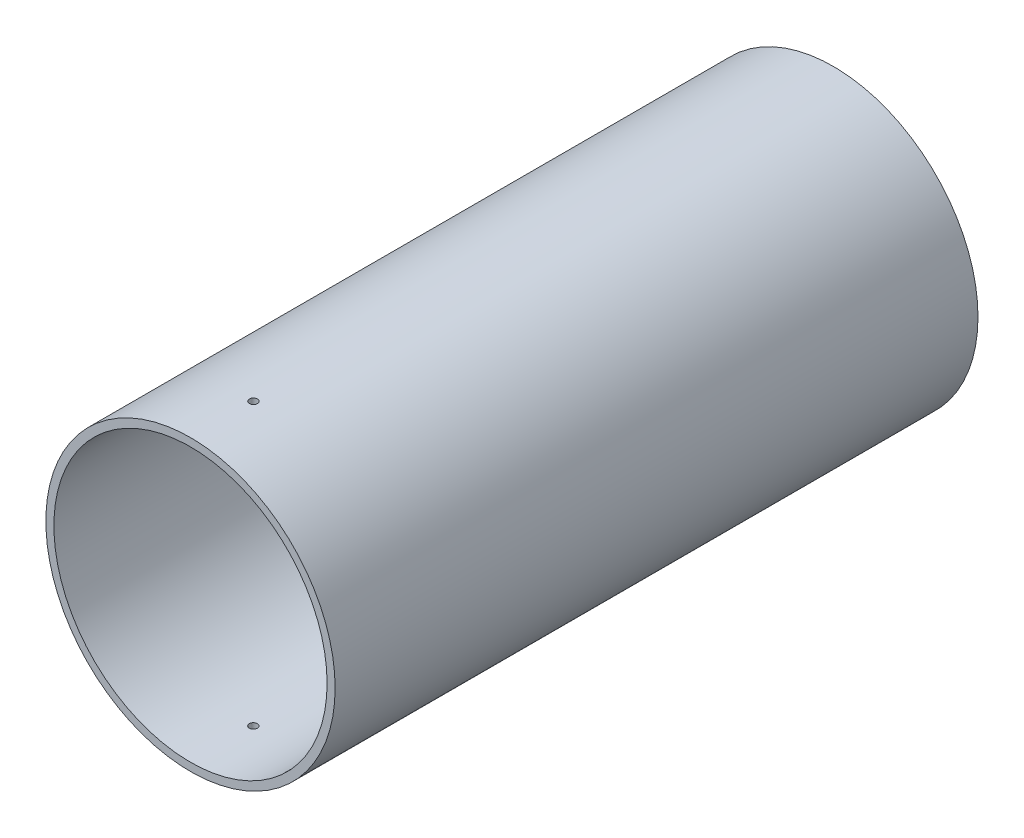
SolidWorks part; units mm, degrees
material "AISI 316 Stainless Steel Sheet (SS)"
ref_plane "Front Plane" through (0, 0, 0) normal (0, 0, 1) x (1, 0, 0)
ref_plane "Top Plane" through (0, 0, 0) normal (0, 1, 0) x (1, 0, 0)
ref_plane "Right Plane" through (0, 0, 0) normal (1, 0, 0) x (0, 0, -1)
sketch "Sketch2" plane through (0, 0, 0) normal (0, 0, 1) x (1, 0, 0)
  circle A0 centre (0, 0) radius 114.3
  dimension "D1" = 228.6
extrude "Boss-Extrude2" add sketch "Sketch2" along normal blind 508
sketch "Sketch3" plane through (0, 0, 508) normal (0, 0, 1) x (1, 0, 0)
  circle A0 centre (0, 0) radius 107.95
  dimension "D1" = 215.9
extrude "Cut-Extrude1" cut sketch "Sketch3" against normal blind 495.3
sketch "Sketch4" plane through (0, 0, 0) normal (0, 1, 0) x (1, 0, 0)
  circle A0 centre (0, -458.3117) radius 3.175
  point P2 (0, 0)
extrude "Cut-Extrude2" cut sketch "Sketch4" against normal through all both and the other way through all
